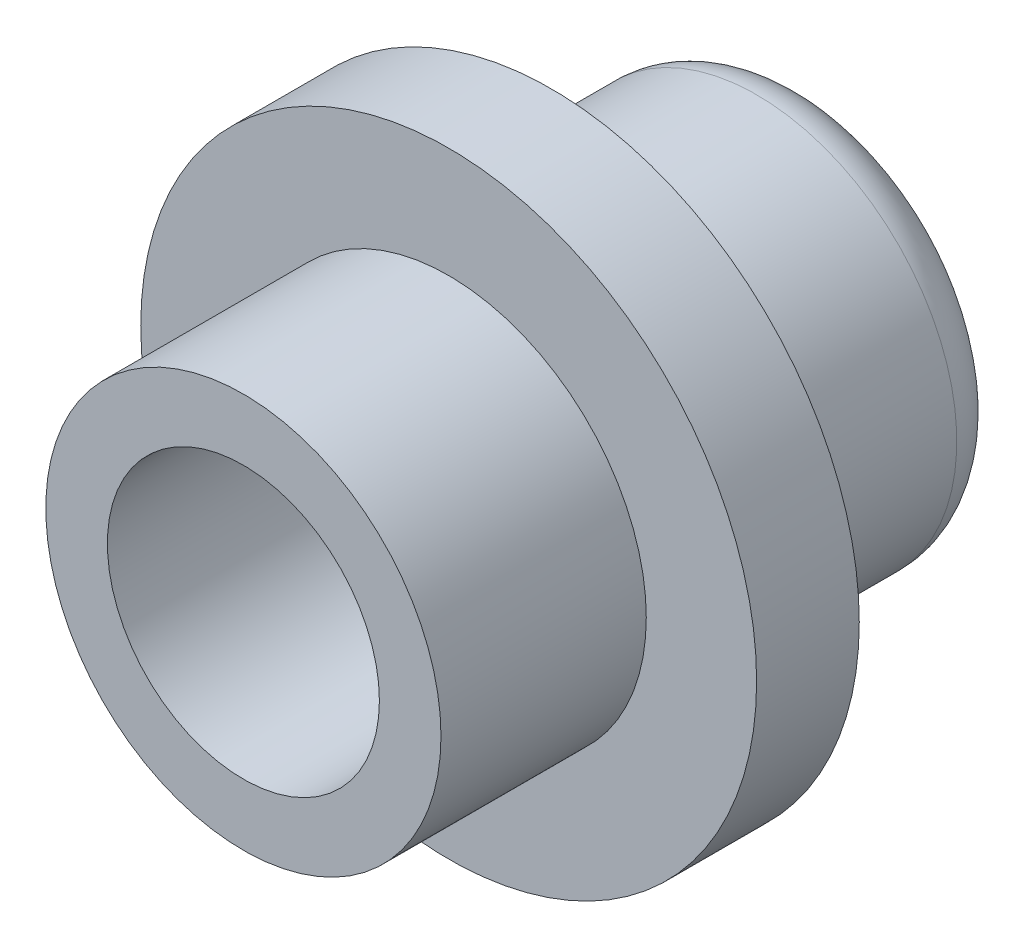
SolidWorks part; units mm, degrees
ref_plane "Front Plane" through (0, 0, 0) normal (0, 0, 1) x (1, 0, 0)
ref_plane "Top Plane" through (0, 0, 0) normal (0, 1, 0) x (1, 0, 0)
ref_plane "Right Plane" through (0, 0, 0) normal (1, 0, 0) x (0, 0, -1)
sketch "Sketch1" plane through (0, 0, 0) normal (0, 0, 1) x (1, 0, 0)
  circle A0 centre (0, 0) radius 2.65
  circle A1 centre (0, 0) radius 3.9
  dimension "D1" = 5.3
  dimension "D2" = 7.8
extrude "Boss-Extrude1" add sketch "Sketch1" along normal blind 5
sketch "Sketch2" plane through (0, 0, 5) normal (0, 0, 1) x (1, 0, 0)
  circle A0 centre (0, 0) radius 2.65
  circle A1 centre (0, 0) radius 6
  dimension "D1" = 12
extrude "Boss-Extrude2" add sketch "Sketch2" against normal blind 2
sketch "Sketch3" plane through (0, 0, 0) normal (0, 0, -1) x (-1, 0, 0)
  circle A0 centre (0, 0) radius 3.9
extrude "Boss-Extrude3" add sketch "Sketch3" along normal blind 2
fillet "Fillet1" radius 1 1 edges at (-3.9, 0, -2)
sketch "Sketch4" plane through (0, 0, 5) normal (0, 0, 1) x (1, 0, 0)
  circle A0 centre (0, 0) radius 2.65
  circle A1 centre (0, 0) radius 3.85
  dimension "D1" = 7.7
extrude "Boss-Extrude4" add sketch "Sketch4" along normal blind 4
